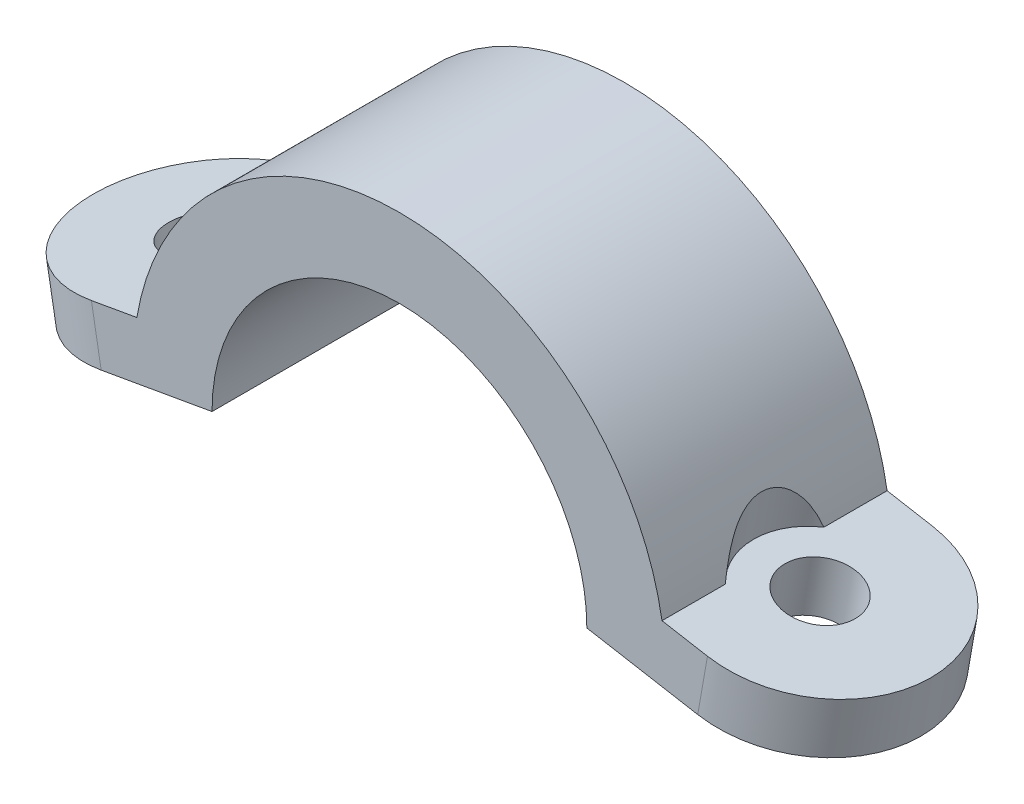
SolidWorks part; units mm, degrees
ref_plane "Front Plane" through (0, 0, 0) normal (0, 0, 1) x (1, 0, 0)
ref_plane "Top Plane" through (0, 0, 0) normal (0, 1, 0) x (1, 0, 0)
ref_plane "Right Plane" through (0, 0, 0) normal (1, 0, 0) x (0, 0, -1)
sketch "Sketch1" plane through (0, 0, 0) normal (0, 0, 1) x (1, 0, 0)
  line L1 (16.65, 0) -> (23.6181, -1.2287)
  line L2 (-16.65, 0) -> (-23.6181, -1.2287)
  arc A0 (16.65, 0) -> (-16.65, 0) centre (0, 0) ccw
  arc A1 (23.6181, -1.2287) -> (-23.6181, -1.2287) centre (0, 0) ccw
  dimension "D1" = 33.3
  dimension "D2" = 7
extrude "Boss-Extrude1" add sketch "Sketch1" along normal blind 20
sketch "Sketch2" plane through (0.5021, 2.8473, 0) normal (-0.1736, -0.9848, 0) x (-0.9848, 0.1736, 0)
  line L4 (-26.397, 0) -> (-16.397, 0)
  line L5 (-16.397, 0) -> (-16.397, -20)
  line L6 (-16.397, -20) -> (-26.397, -20)
  arc A1 (-26.397, 0) -> (-26.397, -20) centre (-26.397, -10) ccw
  dimension "D1" = 10
extrude "Boss-Extrude2" add sketch "Sketch2" against normal blind 5
sketch "Sketch6" plane through (-0.5021, 2.8473, 0) normal (0.1736, -0.9848, 0) x (0.9848, 0.1736, 0)
  line L1 (-26.397, 20) -> (-16.397, 20)
  line L2 (-16.397, 20) -> (-16.397, 0)
  line L3 (-16.397, 0) -> (-26.397, 0)
  arc A0 (-26.397, 20) -> (-26.397, 0) centre (-26.397, 10) ccw
extrude "Boss-Extrude4" add sketch "Sketch6" against normal blind 5
sketch "Sketch8" plane through (-1.3703, 7.7714, 0) normal (-0.1736, 0.9848, 0) x (0.9848, 0.1736, 0)
  circle A0 centre (-26.397, -10) radius 3.175
extrude "Cut-Extrude2" cut sketch "Sketch8" against normal through all
sketch "Sketch9" plane through (-1.3703, 7.7714, 0) normal (-0.1736, 0.9848, 0) x (0.9848, 0.1736, 0)
  circle A0 centre (-26.397, -10) radius 6
extrude "Cut-Extrude3" cut sketch "Sketch9" along normal blind 5
sketch "Sketch10" plane through (1.3703, 7.7714, 0) normal (0.1736, 0.9848, 0) x (0.9848, -0.1736, 0)
  circle A0 centre (26.397, -10) radius 3.175
extrude "Cut-Extrude4" cut sketch "Sketch10" against normal through all
sketch "Sketch11" plane through (1.3703, 7.7714, 0) normal (0.1736, 0.9848, 0) x (0.9848, -0.1736, 0)
  circle A0 centre (26.397, -10) radius 6
extrude "Cut-Extrude5" cut sketch "Sketch11" along normal blind 5
